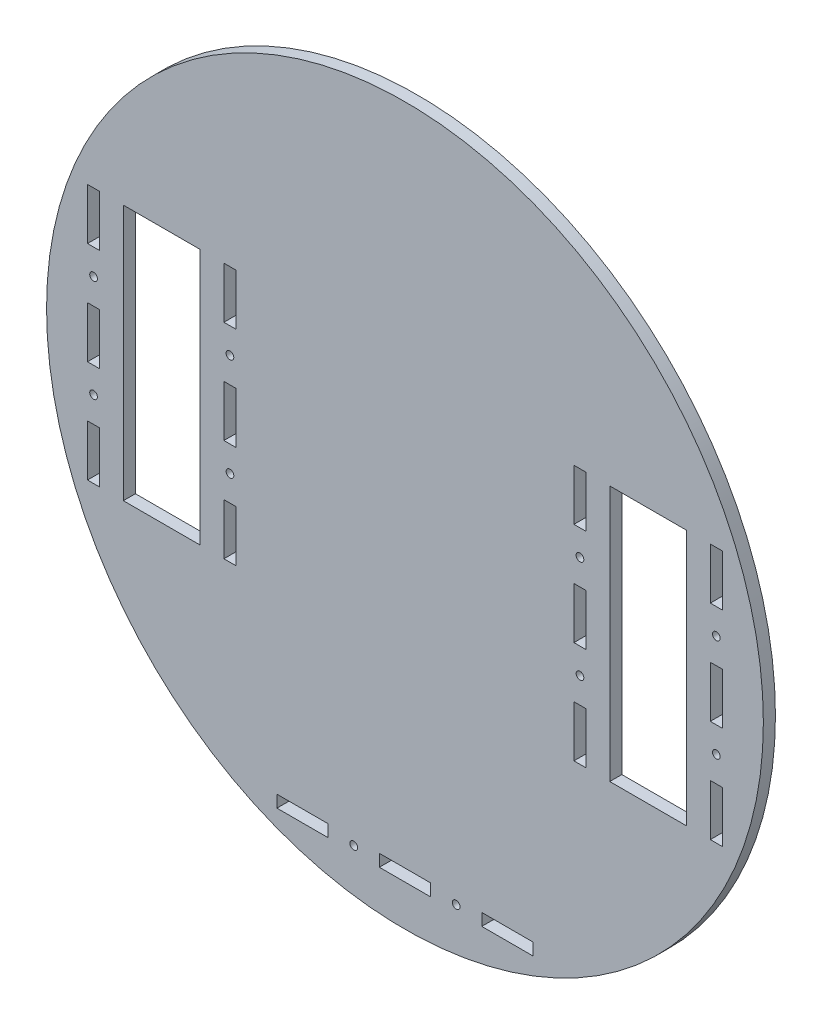
SolidWorks part; units mm, degrees
ref_plane "Front Plane" through (0, 0, 0) normal (0, 0, 1) x (1, 0, 0)
ref_plane "Top Plane" through (0, 0, 0) normal (0, 1, 0) x (1, 0, 0)
ref_plane "Right Plane" through (0, 0, 0) normal (1, 0, 0) x (0, 0, -1)
sketch "Sketch1" plane through (0, 0, 0) normal (0, 0, 1) x (1, 0, 0)
  line L0 (0, 177.8) -> (0, -177.8) construction
  line L1 (-177.8, 0) -> (177.8, 0) construction
  circle A0 centre (0, 0) radius 177.8
  dimension "D1" = 355.6
extrude "Boss-Extrude1" add sketch "Sketch1" along normal blind 5.9944
sketch "Sketch3" plane through (0, 0, 5.9944) normal (0, 0, 1) x (1, 0, 0)
  line L0 (0, 177.8) -> (0, -177.8) construction
  line L1 (-177.8, 0) -> (177.8, 0) construction
  line L2 (-151.4856, -63.5) -> (-151.4856, -38.1)
  line L3 (-139.7, 63.5) -> (-101.6, 63.5)
  line L4 (-139.7, 63.5) -> (-139.7, -63.5)
  line L5 (-139.7, -63.5) -> (-101.6, -63.5)
  line L6 (-101.6, 63.5) -> (-101.6, -63.5)
  line L7 (-157.48, 63.5) -> (-151.4856, 63.5)
  line L8 (-157.48, 63.5) -> (-157.48, 38.1)
  line L9 (-157.48, 38.1) -> (-151.4856, 38.1)
  line L10 (-151.4856, 63.5) -> (-151.4856, 38.1)
  line L11 (-157.48, -38.1) -> (-151.4856, -38.1)
  line L12 (-157.48, -63.5) -> (-157.48, -38.1)
  line L13 (-157.48, -63.5) -> (-151.4856, -63.5)
  line L14 (-157.48, 12.7) -> (-151.4856, 12.7)
  line L15 (-157.48, 12.7) -> (-157.48, -12.7)
  line L16 (-157.48, -12.7) -> (-151.4856, -12.7)
  line L17 (-151.4856, 12.7) -> (-151.4856, -12.7)
  line L18 (151.4856, 12.7) -> (151.4856, -12.7)
  line L19 (157.48, -12.7) -> (151.4856, -12.7)
  line L20 (157.48, 12.7) -> (157.48, -12.7)
  line L21 (157.48, 12.7) -> (151.4856, 12.7)
  line L22 (157.48, -63.5) -> (151.4856, -63.5)
  line L23 (157.48, -63.5) -> (157.48, -38.1)
  line L24 (157.48, -38.1) -> (151.4856, -38.1)
  line L25 (151.4856, 63.5) -> (151.4856, 38.1)
  line L26 (157.48, 38.1) -> (151.4856, 38.1)
  line L27 (157.48, 63.5) -> (157.48, 38.1)
  line L28 (157.48, 63.5) -> (151.4856, 63.5)
  line L29 (101.6, 63.5) -> (101.6, -63.5)
  line L30 (139.7, -63.5) -> (101.6, -63.5)
  line L31 (139.7, 63.5) -> (139.7, -63.5)
  line L32 (139.7, 63.5) -> (101.6, 63.5)
  line L33 (151.4856, -63.5) -> (151.4856, -38.1)
  line L34 (-120.65, 130.6002) -> (-120.65, -130.6002) construction
  line L35 (-89.8144, 12.7) -> (-89.8144, -12.7)
  line L36 (-83.82, -12.7) -> (-89.8144, -12.7)
  line L37 (-83.82, 12.7) -> (-83.82, -12.7)
  line L38 (-83.82, 12.7) -> (-89.8144, 12.7)
  line L39 (-83.82, -63.5) -> (-89.8144, -63.5)
  line L40 (-83.82, -63.5) -> (-83.82, -38.1)
  line L41 (-83.82, -38.1) -> (-89.8144, -38.1)
  line L42 (-89.8144, 63.5) -> (-89.8144, 38.1)
  line L43 (-83.82, 38.1) -> (-89.8144, 38.1)
  line L44 (-83.82, 63.5) -> (-83.82, 38.1)
  line L45 (-83.82, 63.5) -> (-89.8144, 63.5)
  line L46 (-89.8144, -63.5) -> (-89.8144, -38.1)
  line L47 (89.8144, -63.5) -> (89.8144, -38.1)
  line L48 (83.82, 63.5) -> (89.8144, 63.5)
  line L49 (83.82, 63.5) -> (83.82, 38.1)
  line L50 (83.82, 38.1) -> (89.8144, 38.1)
  line L51 (89.8144, 63.5) -> (89.8144, 38.1)
  line L52 (83.82, -38.1) -> (89.8144, -38.1)
  line L53 (83.82, -63.5) -> (83.82, -38.1)
  line L54 (83.82, -63.5) -> (89.8144, -63.5)
  line L55 (83.82, 12.7) -> (89.8144, 12.7)
  line L56 (83.82, 12.7) -> (83.82, -12.7)
  line L57 (83.82, -12.7) -> (89.8144, -12.7)
  line L58 (89.8144, 12.7) -> (89.8144, -12.7)
  line L59 (-63.5, 151.4856) -> (-38.1, 151.4856) [skipped]
  line L60 (63.5, 157.48) -> (63.5, 151.4856) [skipped]
  line L61 (63.5, 157.48) -> (38.1, 157.48) [skipped]
  line L62 (38.1, 157.48) -> (38.1, 151.4856) [skipped]
  line L63 (63.5, 151.4856) -> (38.1, 151.4856) [skipped]
  line L64 (-38.1, 157.48) -> (-38.1, 151.4856) [skipped]
  line L65 (-63.5, 157.48) -> (-38.1, 157.48) [skipped]
  line L66 (-63.5, 157.48) -> (-63.5, 151.4856) [skipped]
  line L67 (12.7, 157.48) -> (12.7, 151.4856) [skipped]
  line L68 (12.7, 157.48) -> (-12.7, 157.48) [skipped]
  line L69 (-12.7, 157.48) -> (-12.7, 151.4856) [skipped]
  line L70 (12.7, 151.4856) -> (-12.7, 151.4856) [skipped]
  line L71 (151.4856, 63.5) -> (151.4856, 38.1) [skipped]
  line L72 (157.48, -63.5) -> (151.4856, -63.5) [skipped]
  line L73 (157.48, -63.5) -> (157.48, -38.1) [skipped]
  line L74 (157.48, -38.1) -> (151.4856, -38.1) [skipped]
  line L75 (151.4856, -63.5) -> (151.4856, -38.1) [skipped]
  line L76 (157.48, 38.1) -> (151.4856, 38.1) [skipped]
  line L77 (157.48, 63.5) -> (157.48, 38.1) [skipped]
  line L78 (157.48, 63.5) -> (151.4856, 63.5) [skipped]
  line L79 (157.48, -12.7) -> (151.4856, -12.7) [skipped]
  line L80 (157.48, -12.7) -> (157.48, 12.7) [skipped]
  line L81 (157.48, 12.7) -> (151.4856, 12.7) [skipped]
  line L82 (151.4856, -12.7) -> (151.4856, 12.7) [skipped]
  line L83 (63.5, -151.4856) -> (38.1, -151.4856)
  line L84 (-63.5, -157.48) -> (-63.5, -151.4856)
  line L85 (-63.5, -157.48) -> (-38.1, -157.48)
  line L86 (-38.1, -157.48) -> (-38.1, -151.4856)
  line L87 (-63.5, -151.4856) -> (-38.1, -151.4856)
  line L88 (38.1, -157.48) -> (38.1, -151.4856)
  line L89 (63.5, -157.48) -> (38.1, -157.48)
  line L90 (63.5, -157.48) -> (63.5, -151.4856)
  line L91 (-12.7, -157.48) -> (-12.7, -151.4856)
  line L92 (-12.7, -157.48) -> (12.7, -157.48)
  line L93 (12.7, -157.48) -> (12.7, -151.4856)
  line L94 (-12.7, -151.4856) -> (12.7, -151.4856)
  line L95 (-154.4828, 38.1) -> (-154.4828, 25.4) construction
  circle A0 centre (0, 0) radius 177.8 construction
  circle A1 centre (-154.4828, 25.4) radius 1.905
  circle A2 centre (-154.4828, -25.4) radius 1.905
  circle A3 centre (-86.8172, -25.4) radius 1.905
  circle A4 centre (-86.8172, 25.4) radius 1.905
  circle A5 centre (86.8172, -25.4) radius 1.905
  circle A6 centre (154.4828, -25.4) radius 1.905
  circle A7 centre (86.8172, 25.4) radius 1.905
  circle A8 centre (154.4828, 25.4) radius 1.905
  circle A9 centre (25.4, 154.4828) radius 1.905 [skipped]
  circle A10 centre (-25.4, 154.4828) radius 1.905 [skipped]
  circle A11 centre (154.4828, -25.4) radius 1.905 [skipped]
  circle A12 centre (154.4828, 25.4) radius 1.905 [skipped]
  circle A13 centre (-25.4, -154.4828) radius 1.905
  circle A14 centre (25.4, -154.4828) radius 1.905
  point P11 (-101.6, 0)
  point P16 (-151.4856, 0)
  point P43 (-120.65, 63.5)
  point P70 (-154.4828, 38.1)
  point P107 (0, 0)
  point P138 (0, 0)
  dimension "D11" = 3.81
  dimension "D1" = 38.1
  dimension "D2" = 127
  dimension "D3" = 101.6
  dimension "D4" = 25.4
  dimension "D5" = 5.9944
  dimension "D6" = 25.4
  dimension "D7" = 5.9944
  dimension "D8" = 20.32
  dimension "D9" = 38.1
  dimension "D12" = 12.7
  dimension "D10" = 4
  dimension "D13" = 4
extrude "Cut-Extrude1" cut sketch "Sketch3" against normal blind 5.9944
